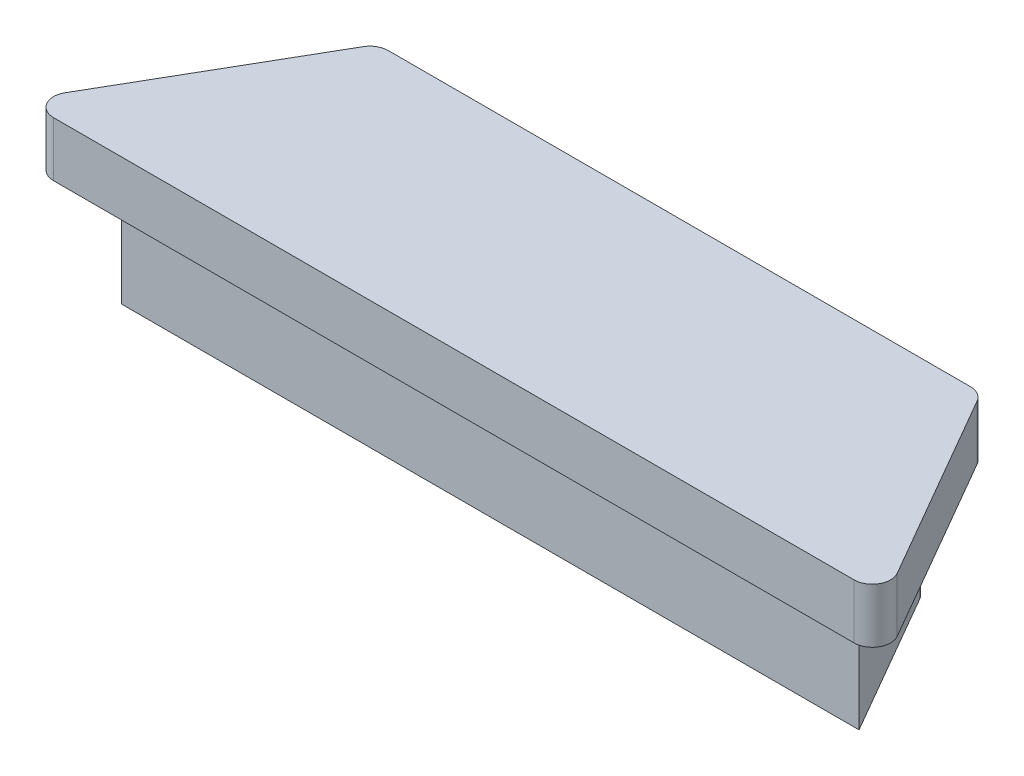
SolidWorks part; units mm, degrees
ref_plane "Front Plane" through (0, 0, 0) normal (0, 0, 1) x (1, 0, 0)
ref_plane "Top Plane" through (0, 0, 0) normal (0, 1, 0) x (1, 0, 0)
ref_plane "Right Plane" through (0, 0, 0) normal (1, 0, 0) x (0, 0, -1)
sketch "Sketch1" plane through (0, 0, 0) normal (0, 1, 0) x (1, 0, 0)
  line L0 (-21.043, 71.8226) -> (-50.7151, 71.8226)
  line L1 (-56.1327, 63.4389) -> (-51.5811, 71.3226)
  line L2 (-15.6253, 63.4389) -> (-56.1327, 63.4389)
  line L3 (-15.6253, 63.4389) -> (-20.1769, 71.3226)
  arc A0 (-21.043, 71.8226) -> (-20.1769, 71.3226) centre (-21.043, 70.8226) cw
  arc A1 (-50.7151, 71.8226) -> (-51.5811, 71.3226) centre (-50.7151, 70.8226) ccw
extrude "Boss-Extrude1" add sketch "Sketch1" along normal blind 6
sketch "Sketch2" plane through (0, 6, 0) normal (0, 1, 0) x (1, 0, 0)
  line L2 (-13.8932, 61.4389) -> (-57.8648, 61.4389)
  line L5 (-52.7358, 73.3226) -> (-58.7308, 62.9389)
  line L9 (-51.8698, 73.8226) -> (-19.8883, 73.8226)
  line L10 (-13.0272, 62.9389) -> (-19.0222, 73.3226)
  arc A0 (-58.7308, 62.9389) -> (-57.8648, 61.4389) centre (-57.8648, 62.4389) ccw
  arc A1 (-13.0272, 62.9389) -> (-13.8932, 61.4389) centre (-13.8932, 62.4389) cw
  arc A2 (-19.0222, 73.3226) -> (-19.8883, 73.8226) centre (-19.8883, 72.8226) ccw
  arc A3 (-51.8698, 73.8226) -> (-52.7358, 73.3226) centre (-51.8698, 72.8226) ccw
  dimension "D1" = 1
extrude "Boss-Extrude2" add sketch "Sketch2" along normal blind 3
